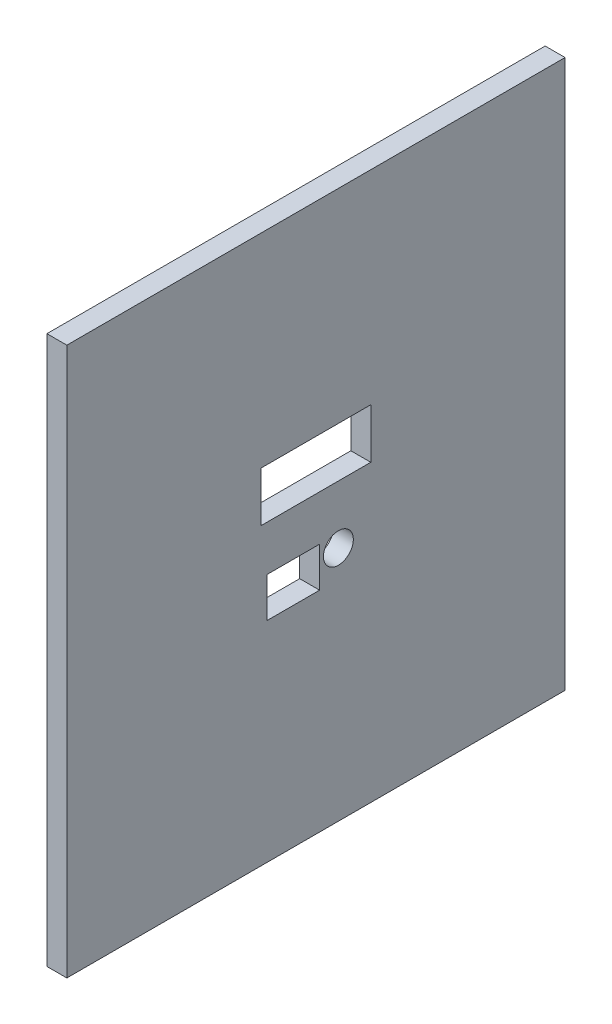
SolidWorks part; units mm, degrees
ref_plane "Front Plane" through (0, 0, 0) normal (0, 0, 1) x (1, 0, 0)
ref_plane "Top Plane" through (0, 0, 0) normal (0, 1, 0) x (1, 0, 0)
ref_plane "Right Plane" through (0, 0, 0) normal (1, 0, 0) x (0, 0, -1)
sketch "Sketch1" plane through (0, 0, 0) normal (1, 0, 0) x (0, 0, -1)
  line L1 (25, -27.5) -> (-25, -27.5)
  line L2 (25, -27.5) -> (25, 27.5)
  line L3 (25, 27.5) -> (-25, 27.5)
  line L4 (-25, -27.5) -> (-25, 27.5)
  line L5 (25, -27.5) -> (-25, 27.5) construction
  line L6 (25, 27.5) -> (-25, -27.5) construction
  point P0 (0, 0)
  dimension "D1" = 50
  dimension "D2" = 55
extrude "Boss-Extrude1" add sketch "Sketch1" along normal blind 2
sketch "Sketch2" plane through (2, 0, 0) normal (1, 0, 0) x (0, 0, -1)
  line L0 (0, 0) -> (0, 6.75) construction
  line L1 (5.25, -6.75) -> (-5.25, -6.75)
  line L2 (5.25, -6.75) -> (5.25, 6.75)
  line L3 (5.25, 6.75) -> (-5.25, 6.75)
  line L4 (-5.25, -6.75) -> (-5.25, 6.75)
  line L5 (5.25, -6.75) -> (-5.25, 6.75) construction
  line L6 (5.25, 6.75) -> (-5.25, -6.75) construction
  line L8 (5.5, 2.0714) -> (-5.5, 2.0714)
  line L9 (5.5, 2.0714) -> (5.5, 7.0714)
  line L10 (5.5, 7.0714) -> (-5.5, 7.0714)
  line L11 (-5.5, 2.0714) -> (-5.5, 7.0714)
  line L12 (5.5, 2.0714) -> (-5.5, 7.0714) construction
  line L13 (5.5, 7.0714) -> (-5.5, 2.0714) construction
  line L14 (0.3657, -6.4768) -> (-4.9343, -6.4768)
  line L15 (0.3657, -6.4768) -> (0.3657, -2.4768)
  line L16 (0.3657, -2.4768) -> (-4.9343, -2.4768)
  line L17 (-4.9343, -6.4768) -> (-4.9343, -2.4768)
  line L18 (0.3657, -6.4768) -> (-4.9343, -2.4768) construction
  line L19 (0.3657, -2.4768) -> (-4.9343, -6.4768) construction
  circle A0 centre (2.25, -3.75) radius 1.5
  point P0 (0, 0)
  point P8 (0, 4.5714)
  point P13 (-2.2843, -4.4768)
  dimension "D7" = 3
  dimension "D9" = 3
  dimension "D1" = 13.5
  dimension "D2" = 10.5
  dimension "D3" = 5
  dimension "D4" = 11
  dimension "D5" = 4
  dimension "D6" = 5.3
  dimension "D8" = 3
extrude "Cut-Extrude1" cut sketch "Sketch2" against normal blind 10 contours L17 L14 L15 L16 | A0 | L11 L8 L4 L3 L2 L9 L10 | L8 L2 L3 L4
